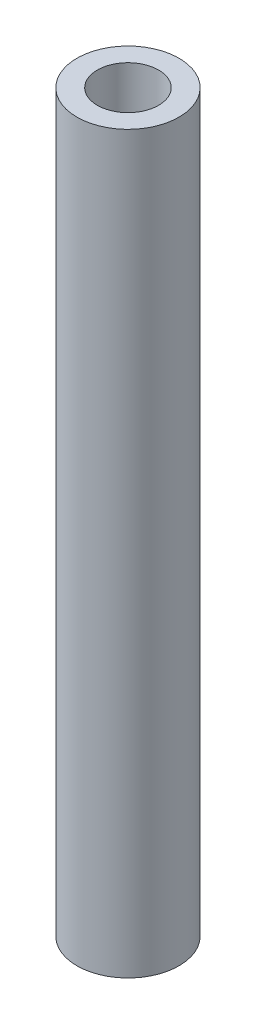
SolidWorks part; units mm, degrees
material "Thornel Mat VMA"
ref_plane "Front Plane" through (0, 0, 0) normal (0, 0, 1) x (1, 0, 0)
ref_plane "Top Plane" through (0, 0, 0) normal (0, 1, 0) x (1, 0, 0)
ref_plane "Right Plane" through (0, 0, 0) normal (1, 0, 0) x (0, 0, -1)
sketch "Sketch1" plane through (0, 0, 0) normal (0, 1, 0) x (1, 0, 0)
  circle A0 centre (0, 0) radius 7.9375
  circle A1 centre (0, 0) radius 4.7625
  dimension "D1" = 15.875
  dimension "D2" = 9.525
extrude "Boss-Extrude1" add sketch "Sketch1" along normal blind 114.3
